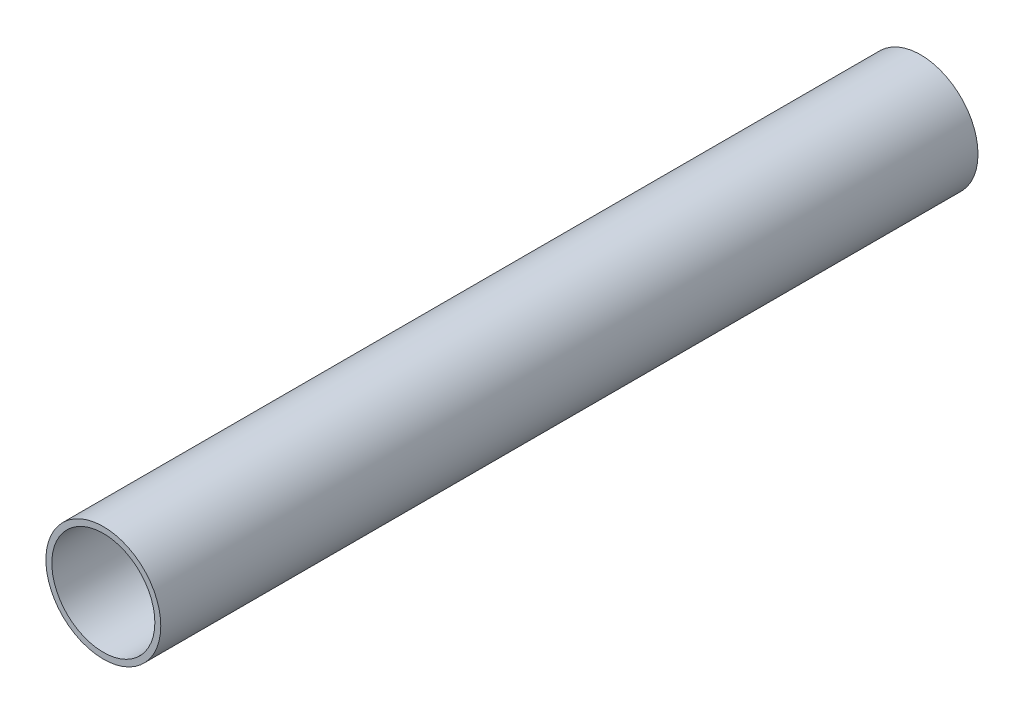
SolidWorks part; units mm, degrees
ref_plane "Front Plane" through (0, 0, 0) normal (0, 0, 1) x (1, 0, 0)
ref_plane "Top Plane" through (0, 0, 0) normal (0, 1, 0) x (1, 0, 0)
ref_plane "Right Plane" through (0, 0, 0) normal (1, 0, 0) x (0, 0, -1)
sketch "Sketch1" plane through (0, 0, 0) normal (0, 0, 1) x (1, 0, 0)
  circle A0 centre (0, 0) radius 21.75
  circle A1 centre (0, 0) radius 24.25
  dimension "D1" = 43.5
  dimension "D2" = 48.5
extrude "Boss-Extrude1" add sketch "Sketch1" against normal blind 345
